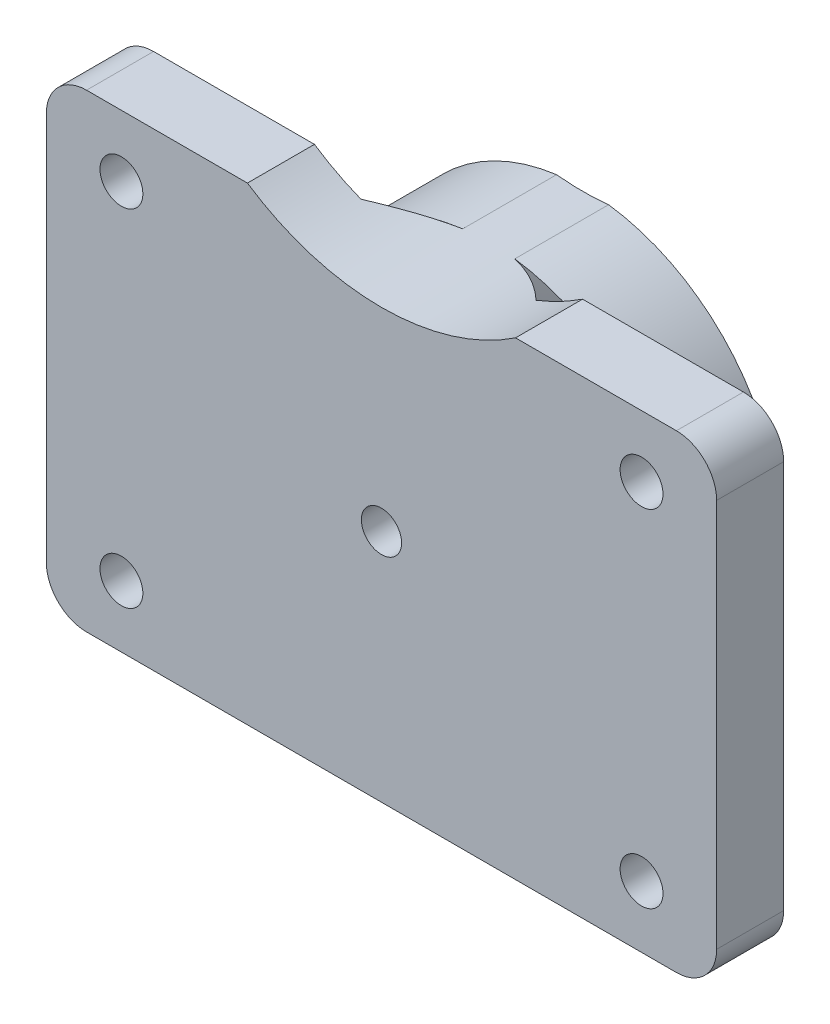
SolidWorks part; units mm, degrees
ref_plane "Alzado" through (0, 0, 0) normal (0, 0, 1) x (1, 0, 0)
ref_plane "Planta" through (0, 0, 0) normal (0, 1, 0) x (1, 0, 0)
ref_plane "Vista lateral" through (0, 0, 0) normal (1, 0, 0) x (0, 0, -1)
sketch "Croquis1" plane through (0, 0, 0) normal (0, 0, 1) x (1, 0, 0)
  line L0 (-21, 12.9) -> (-21, 22.8447) construction
  line L1 (-22, -17.5) -> (22, -17.5)
  line L2 (-25, -14.5) -> (-25, 14.5)
  line L3 (-22, 17.5) -> (22, 17.5)
  line L4 (25, -14.5) -> (25, 14.5)
  line L5 (-25, -17.5) -> (25, 17.5) construction
  line L6 (-25, 17.5) -> (25, -17.5) construction
  line L7 (-19.4, 14.5) -> (-29.4687, 14.5) construction
  line L8 (0, 37.5796) -> (0, -45.1336) construction
  line L9 (44.7441, 0) -> (-40.1458, 0) construction
  circle A0 centre (-19.4, 12.9) radius 1.6
  circle A1 centre (19.4, 12.9) radius 1.6
  circle A2 centre (19.4, -12.9) radius 1.6
  circle A3 centre (-19.4, -12.9) radius 1.6
  arc A4 (-22, -17.5) -> (-25, -14.5) centre (-22, -14.5) cw
  arc A5 (22, -17.5) -> (25, -14.5) centre (22, -14.5) ccw
  arc A6 (22, 17.5) -> (25, 14.5) centre (22, 14.5) cw
  arc A7 (-25, 14.5) -> (-22, 17.5) centre (-22, 14.5) cw
  point P0 (0, 0)
  dimension "D3" = 3.2
  dimension "D6" = 3
  dimension "D1" = 50
  dimension "D2" = 35
  dimension "D4" = 4
  dimension "D5" = 3
extrude "Saliente-Extruir1" add sketch "Croquis1" along normal mid plane 5
sketch "Croquis2" plane through (0, 0, 0) normal (0, 1, 0) x (1, 0, 0)
  line L0 (0, -7.4176) -> (0, 28.5783) construction
  line L1 (8.2, 2.5) -> (8.2, 12.5)
  line L2 (22, 2.5) -> (-22, 2.5) construction
  line L3 (8.2, 12.5) -> (14.7, 12.5)
  line L4 (14.7, 12.5) -> (14.7, 5.5)
  line L5 (14.7, 5.5) -> (17, 2.5)
  line L6 (17, 2.5) -> (8.2, 2.5)
  dimension "D1" = 10
  dimension "D2" = 8.2
  dimension "D3" = 6.5
  dimension "D4" = 17
  dimension "D5" = 3
revolve "Revolución1" add sketch "Croquis2" angle 360 about L0
sketch "Croquis3" plane through (0, 0, -2.5) normal (0, 0, -1) x (-1, 0, 0)
  circle A0 centre (0, 0) radius 1.5
  dimension "D1" = 3
extrude "Cortar-Extruir1" cut sketch "Croquis3" against normal blind 5
sketch "Croquis4" plane through (0, 0, 2.5) normal (0, 0, 1) x (1, 0, 0)
  line L0 (0, 17.5) -> (0, -17.5) construction
  line L1 (22, 17.5) -> (-22, 17.5) construction
  line L2 (-22, -17.5) -> (22, -17.5) construction
  line L3 (25, 0) -> (-25, 0) construction
  line L4 (25, -14.5) -> (25, 14.5) construction
  line L5 (-25, 14.5) -> (-25, -14.5) construction
  line L6 (-10, 17.5) -> (10, 17.5)
  arc A0 (-10, 17.5) -> (10, 17.5) centre (0, 32.4666) ccw
  dimension "D3" = 18
  dimension "D1" = 15
  dimension "D2" = 15
extrude "Cortar-Extruir2" cut sketch "Croquis4" against normal blind 25
